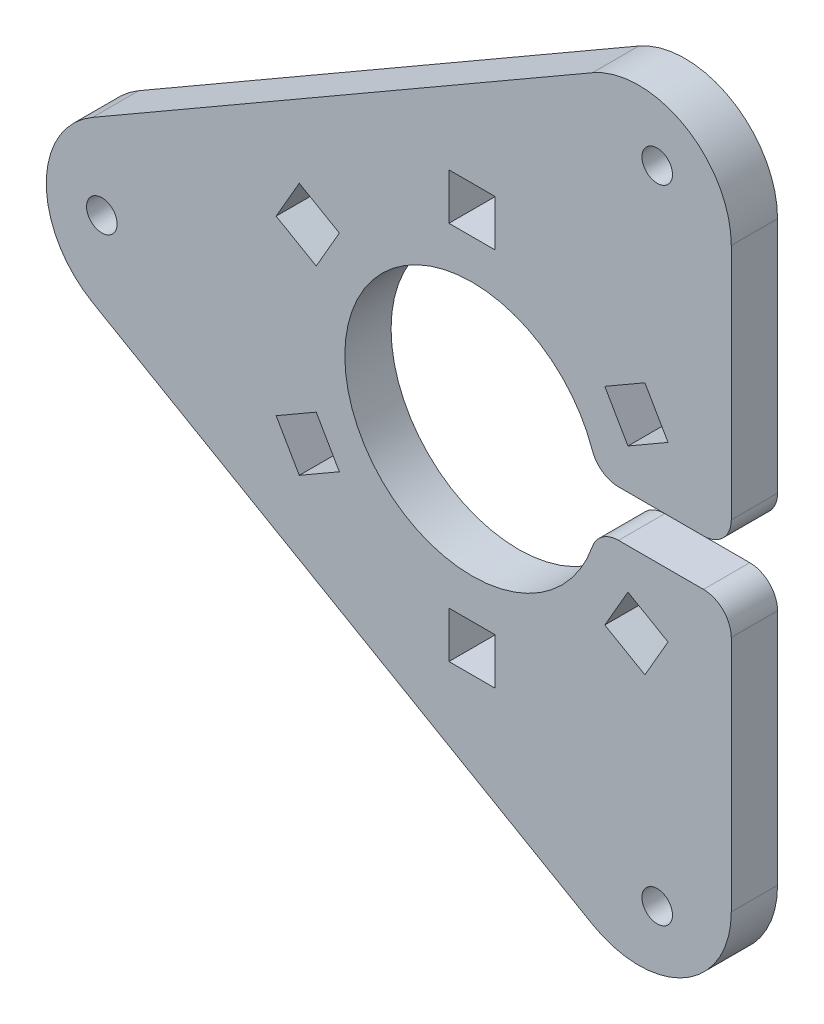
SolidWorks part; units mm, degrees
ref_plane "Front Plane" through (0, 0, 0) normal (0, 0, 1) x (1, 0, 0)
ref_plane "Top Plane" through (0, 0, 0) normal (0, 1, 0) x (1, 0, 0)
ref_plane "Right Plane" through (0, 0, 0) normal (1, 0, 0) x (0, 0, -1)
sketch "Sketch1" plane through (0, 0, 0) normal (0, 0, 1) x (1, 0, 0)
  line L0 (-26, 0) -> (26, 0) construction
  line L7 (-2.5, 23) -> (2.5, 23)
  line L8 (-2.5, 23) -> (-2.5, 18)
  line L9 (-2.5, 18) -> (2.5, 18)
  line L10 (2.5, 23) -> (2.5, 18)
  line L23 (0, 26) -> (0, -26) construction
  line L24 (21.1686, 9.3349) -> (16.8385, 6.8349)
  line L25 (14.3385, 11.1651) -> (16.8385, 6.8349)
  line L26 (18.6686, 13.6651) -> (14.3385, 11.1651)
  line L27 (18.6686, 13.6651) -> (21.1686, 9.3349)
  line L28 (18.6686, -13.6651) -> (14.3385, -11.1651)
  line L29 (16.8385, -6.8349) -> (14.3385, -11.1651)
  line L30 (21.1686, -9.3349) -> (16.8385, -6.8349)
  line L31 (21.1686, -9.3349) -> (18.6686, -13.6651)
  line L32 (-2.5, -23) -> (-2.5, -18)
  line L33 (2.5, -18) -> (-2.5, -18)
  line L34 (2.5, -23) -> (2.5, -18)
  line L35 (2.5, -23) -> (-2.5, -23)
  line L36 (-21.1686, -9.3349) -> (-16.8385, -6.8349)
  line L37 (-14.3385, -11.1651) -> (-16.8385, -6.8349)
  line L38 (-18.6686, -13.6651) -> (-14.3385, -11.1651)
  line L39 (-18.6686, -13.6651) -> (-21.1686, -9.3349)
  line L40 (-18.6686, 13.6651) -> (-14.3385, 11.1651)
  line L41 (-16.8385, 6.8349) -> (-14.3385, 11.1651)
  line L42 (-21.1686, 9.3349) -> (-16.8385, 6.8349)
  line L43 (-21.1686, 9.3349) -> (-18.6686, 13.6651)
  line L44 (28, 2.5) -> (13.5208, 2.5)
  line L45 (28, -2.5) -> (13.5208, -2.5)
  line L46 (28, 48.4974) -> (28, -48.4974) construction
  line L47 (28, -48.4974) -> (-56, 0) construction
  line L48 (-56, 0) -> (28, 48.4974) construction
  line L49 (28, 2.5) -> (28, 48.4974)
  line L50 (28, 48.4974) -> (-56, 0)
  line L51 (-56, 0) -> (28, -48.4974)
  line L52 (28, -48.4974) -> (28, -2.5)
  line L53 (0, 0) -> (28, 48.4974) construction
  circle A0 centre (0, 0) radius 13.75 construction
  arc A2 (13.5208, 2.5) -> (13.5208, -2.5) centre (0, 0) ccw
  circle A4 centre (20, 34.641) radius 1.65
  circle A5 centre (20, -34.641) radius 1.65
  circle A6 centre (-40, 0) radius 1.65
  point P8 (-57.9149, 23)
  point P15 (0, 0)
  point P40 (0, 0)
  point P48 (0, 0)
  point P50 (0, 0)
  dimension "D2" = 28
  dimension "D1" = 27.5
  dimension "D10" = 3.3
  dimension "D3" = 5
  dimension "D4" = 5
  dimension "D5" = 18
  dimension "D6" = 6
  dimension "D7" = 5
  dimension "D9" = 40
  dimension "D11" = 3
  dimension "D8" = 3
extrude "Boss-Extrude1" add sketch "Sketch1" along normal blind 5
fillet "Congé1" radius 10 3 edges at (28, -48.4974, 2.5) (-56, 0, 2.5) (28, 48.4974, 2.5)
fillet "Congé2" radius 3 4 edges at (13.5208, 2.5, 2.5) (13.5208, -2.5, 2.5) (28, -2.5, 2.5) (28, 2.5, 2.5)
